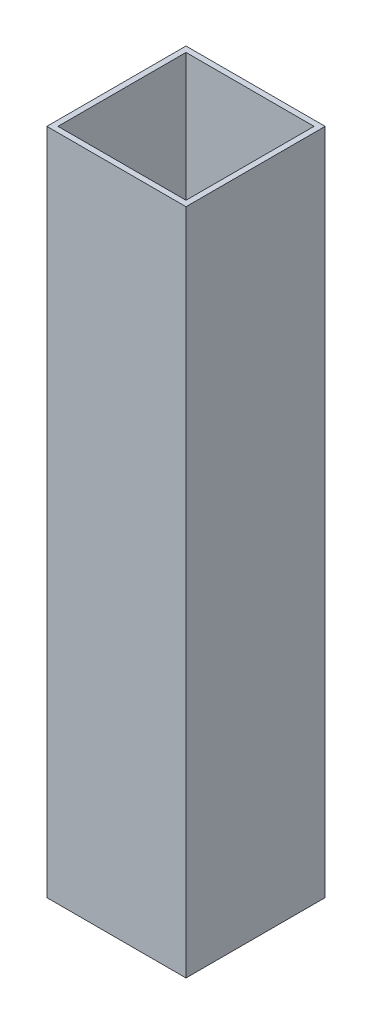
SolidWorks part; units mm, degrees
ref_plane "Front Plane" through (0, 0, 0) normal (0, 0, 1) x (1, 0, 0)
ref_plane "Top Plane" through (0, 0, 0) normal (0, 1, 0) x (1, 0, 0)
ref_plane "Right Plane" through (0, 0, 0) normal (1, 0, 0) x (0, 0, -1)
sketch "Sketch1" plane through (0, 0, 0) normal (0, 1, 0) x (1, 0, 0)
  line L0 (-23, 23) -> (23, 23)
  line L1 (-25, -25) -> (25, -25)
  line L2 (-25, -25) -> (-25, 25)
  line L3 (-25, 25) -> (25, 25)
  line L4 (25, -25) -> (25, 25)
  line L5 (-25, -25) -> (25, 25) construction
  line L6 (-25, 25) -> (25, -25) construction
  line L7 (23, -23) -> (23, 23)
  line L8 (-23, -23) -> (23, -23)
  line L9 (-23, -23) -> (-23, 23)
  point P0 (0, 0)
  dimension "D1" = 50
  dimension "D2" = 2
extrude "Boss-Extrude1" add sketch "Sketch1" along normal blind 240
